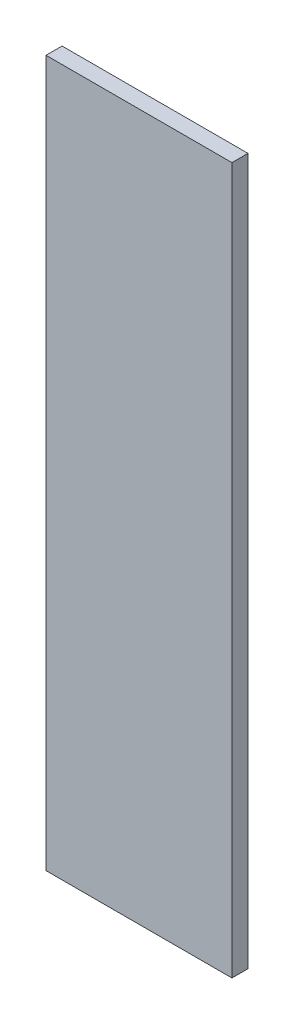
SolidWorks part; units mm, degrees
ref_plane "Front Plane" through (0, 0, 0) normal (0, 0, 1) x (1, 0, 0)
ref_plane "Top Plane" through (0, 0, 0) normal (0, 1, 0) x (1, 0, 0)
ref_plane "Right Plane" through (0, 0, 0) normal (1, 0, 0) x (0, 0, -1)
sketch "Sketch1" plane through (0, 0, 0) normal (0, 0, 1) x (1, 0, 0)
  line L1 (0, 0) -> (220.726, 0)
  line L2 (0, 0) -> (0, 838.2)
  line L3 (0, 838.2) -> (220.726, 838.2)
  line L4 (220.726, 0) -> (220.726, 838.2)
  dimension "D1" = 838.2
  dimension "D2" = 220.726
extrude "Boss-Extrude1" add sketch "Sketch1" along normal blind 19.05
